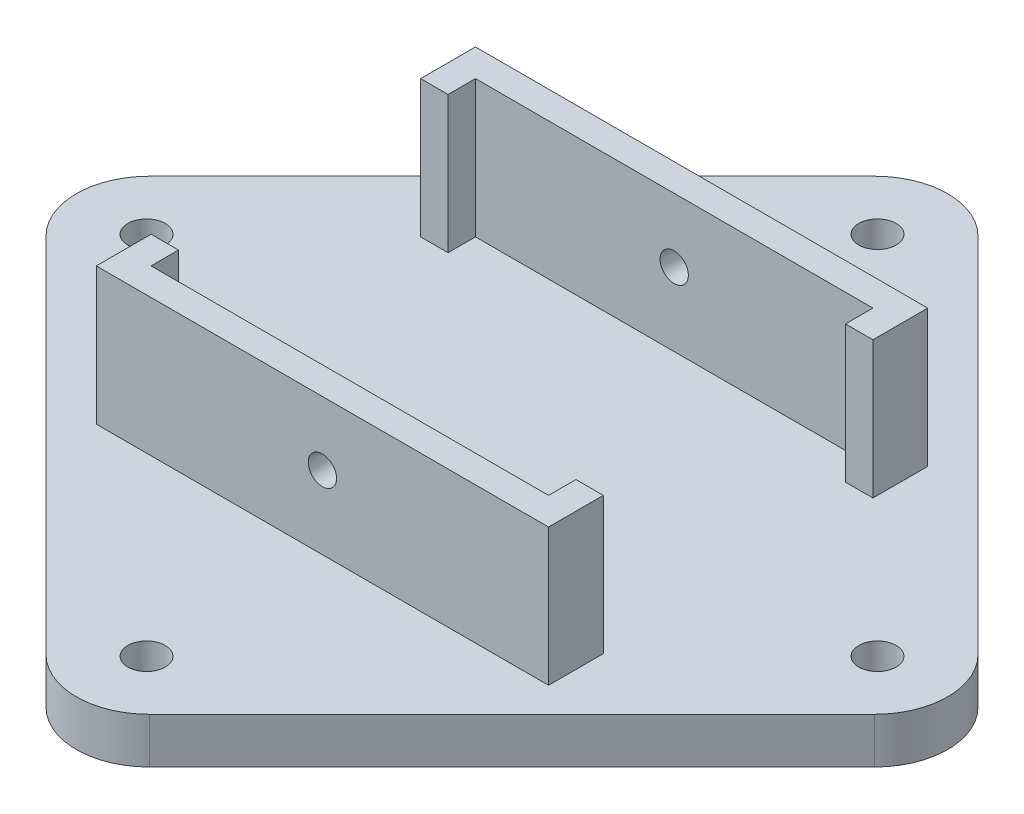
SolidWorks part; units mm, degrees
ref_plane "前视基准面" through (0, 0, 0) normal (0, 0, 1) x (1, 0, 0)
ref_plane "上视基准面" through (0, 0, 0) normal (0, 1, 0) x (1, 0, 0)
ref_plane "右视基准面" through (0, 0, 0) normal (1, 0, 0) x (0, 0, -1)
sketch "草图1" plane through (0, 0, 0) normal (0, 1, 0) x (1, 0, 0)
  line L1 (-5.6569, 45.3431) -> (-45.3431, 5.6569)
  line L2 (-45.3431, -5.6569) -> (-5.6569, -45.3431)
  line L3 (5.6569, -45.3431) -> (45.3431, -5.6569)
  line L4 (45.3431, 5.6569) -> (5.6569, 45.3431)
  circle A0 centre (0, 0) radius 36.0624 construction
  circle A1 centre (0, 40) radius 2.05
  circle A2 centre (40, 0) radius 2.05
  circle A3 centre (0, -40) radius 2.05
  circle A4 centre (-40, 0) radius 2.05
  arc A5 (-45.3431, 5.6569) -> (-45.3431, -5.6569) centre (-39.6863, 0) ccw
  arc A6 (-5.6569, -45.3431) -> (5.6569, -45.3431) centre (0, -39.6863) ccw
  arc A7 (45.3431, 5.6569) -> (45.3431, -5.6569) centre (39.6863, 0) cw
  arc A8 (5.6569, 45.3431) -> (-5.6569, 45.3431) centre (0, 39.6863) ccw
  point P18 (0, 0)
  point P25 (0, 51)
  dimension "D3" = 4.1
  dimension "D5" = 8
  dimension "D1" = 51
  dimension "D4" = 40
  dimension "D2" = 4
extrude "凸台-拉伸1" add sketch "草图1" along normal blind 5
sketch "草图2" plane through (0, 5, 0) normal (0, 1, 0) x (1, 0, 0)
  line L0 (-24.75, 14.75) -> (-21.75, 14.75)
  line L1 (24.75, -20.75) -> (-24.75, -20.75)
  line L2 (24.75, -20.75) -> (24.75, -14.75)
  line L3 (24.75, 20.75) -> (-24.75, 20.75)
  line L4 (-24.75, -20.75) -> (-24.75, -14.75)
  line L5 (24.75, -20.75) -> (-24.75, 20.75) construction
  line L6 (24.75, 20.75) -> (-24.75, -20.75) construction
  line L7 (21.75, -17.75) -> (-21.75, -17.75)
  line L8 (21.75, -17.75) -> (21.75, -14.75)
  line L9 (21.75, 17.75) -> (-21.75, 17.75)
  line L10 (-21.75, -17.75) -> (-21.75, -14.75)
  line L11 (21.75, -17.75) -> (-21.75, 17.75) construction
  line L12 (21.75, 17.75) -> (-21.75, -17.75) construction
  line L13 (0, 0) -> (-10.7692, 0) construction
  line L14 (0, 0) -> (0, 9.6792) construction
  line L15 (-24.75, -14.75) -> (-21.75, -14.75)
  line L16 (24.75, -14.75) -> (21.75, -14.75)
  line L17 (24.75, 14.75) -> (21.75, 14.75)
  line L18 (-21.75, 14.75) -> (-21.75, 17.75)
  line L19 (-24.75, 14.75) -> (-24.75, 20.75)
  line L20 (24.75, 14.75) -> (24.75, 20.75)
  line L21 (21.75, 14.75) -> (21.75, 17.75)
  point P0 (0, 0)
  point P6 (0, 0)
  dimension "D1" = 49.5
  dimension "D2" = 41.5
  dimension "D3" = 3
  dimension "D4" = 3
  dimension "D5" = 6
extrude "凸台-拉伸2" add sketch "草图2" along normal blind 15
sketch "草图3" plane through (0, 0, 20.75) normal (0, 0, 1) x (1, 0, 0)
  line L0 (-24.75, 5) -> (24.75, 5) construction
  line L1 (-5.6569, 0) -> (5.6569, 0) construction
  circle A0 centre (0, 13) radius 1.55
  point P5 (0, 0)
  dimension "D1" = 3.1
  dimension "D2" = 8
extrude "切除-拉伸1" cut sketch "草图3" against normal through all and the other way through all
sketch "草图4" plane through (0, 5, 0) normal (0, 1, 0) x (1, 0, 0)
  line L0 (-19.0222, 0) -> (19.0222, 0) construction
  text T0 "2021.4.9" font "微软雅黑" height 5.5
  point P3 (0, 0)
  point P5 (0, 0)
extrude "凸台-拉伸3" [suppressed] add sketch "草图4" along normal blind 1.5
